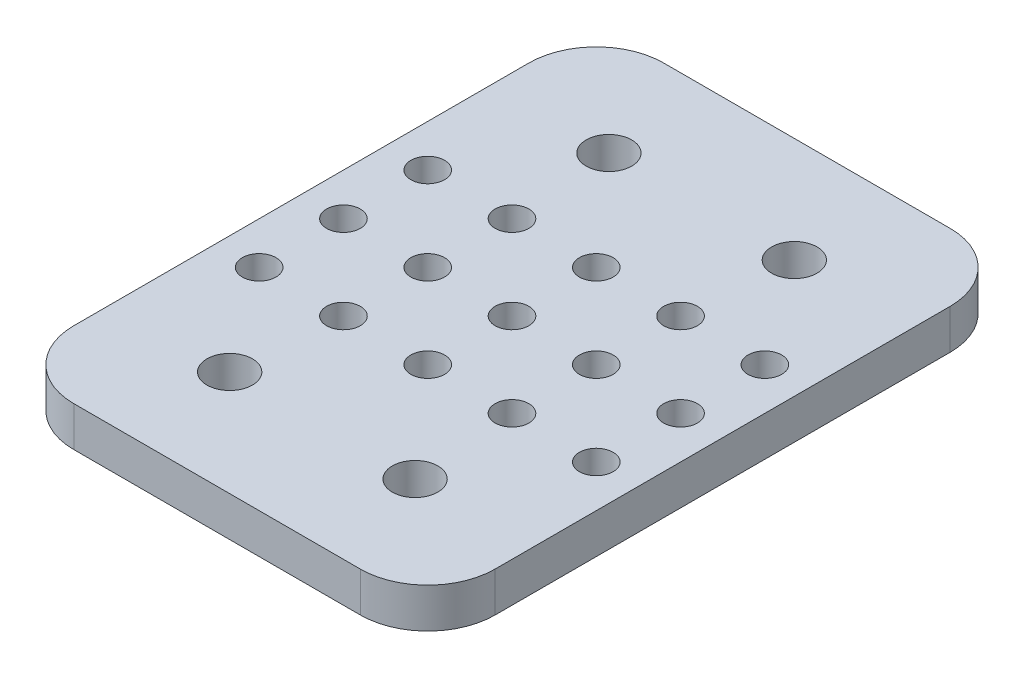
SolidWorks part; units mm, degrees
other "Markup1"
sketch "Sketch3" plane through (0, 6, 0) normal (-0.2556, 0.7181, 0.6473) x (0.9665, 0.2047, 0.1545)
ref_plane "Front Plane" through (0, 0, 0) normal (0, 0, 1) x (1, 0, 0)
ref_plane "Top Plane" through (0, 0, 0) normal (0, 1, 0) x (1, 0, 0)
ref_plane "Right Plane" through (0, 0, 0) normal (1, 0, 0) x (0, 0, -1)
sketch "Sketch1" plane through (0, 0, 0) normal (0, 1, 0) x (1, 0, 0)
  line L0 (31.75, 88.9) -> (31.75, 0) construction
  line L1 (0, 0) -> (63.5, 0)
  line L2 (0, 0) -> (0, 88.9)
  line L3 (0, 88.9) -> (63.5, 88.9)
  line L4 (63.5, 0) -> (63.5, 88.9)
  circle A0 centre (17.78, 73.025) radius 3.429
  circle A1 centre (45.72, 15.875) radius 3.429
  circle A2 centre (17.78, 15.875) radius 3.429
  circle A3 centre (45.72, 73.025) radius 3.429
  dimension "D3" = 57.15
  dimension "D4" = 27.94
  dimension "D5" = 6.858
  dimension "D6" = 15.875
  dimension "D7" = 17.78
  dimension "D1" = 63.5
  dimension "D2" = 88.9
extrude "Boss-Extrude1" add sketch "Sketch1" along normal blind 6
fillet "Fillet1" radius 10.16 4 edges at (0, 3, -88.9) (63.5, 3, -88.9) (63.5, 3, 0) (0, 3, 0)
sketch "Sketch2" plane through (0, 6, 0) normal (0, 1, 0) x (1, 0, 0)
  line L0 (0, 78.74) -> (0, 10.16) construction
  line L1 (0, 19.05) -> (63.5, 19.05) construction
  line L2 (0, 19.05) -> (0, 69.85)
  line L3 (0, 69.85) -> (63.5, 69.85) construction
  line L4 (63.5, 19.05) -> (63.5, 69.85)
  line L5 (63.5, 10.16) -> (63.5, 78.74) construction
  line L6 (53.34, 88.9) -> (10.16, 88.9) construction
  line L7 (6.35, 31.75) -> (19.05, 31.75) construction
  circle A0 centre (6.35, 57.15) radius 2.54
  circle A1 centre (6.35, 44.45) radius 2.54
  circle A2 centre (6.35, 31.75) radius 2.54
  circle A3 centre (19.05, 31.75) radius 2.54
  circle A4 centre (19.05, 44.45) radius 2.54
  circle A5 centre (19.05, 57.15) radius 2.54
  circle A6 centre (31.75, 31.75) radius 2.54
  circle A7 centre (31.75, 44.45) radius 2.54
  circle A8 centre (31.75, 57.15) radius 2.54
  circle A9 centre (44.45, 31.75) radius 2.54
  circle A10 centre (44.45, 44.45) radius 2.54
  circle A11 centre (44.45, 57.15) radius 2.54
  circle A12 centre (57.15, 31.75) radius 2.54
  circle A13 centre (57.15, 44.45) radius 2.54
  circle A14 centre (57.15, 57.15) radius 2.54
  dimension "D3" = 5.08
  dimension "D4" = 12.7
  dimension "D5" = 12.7
  dimension "D6" = 12.7
  dimension "D7" = 6.35
  dimension "D1" = 50.8
  dimension "D2" = 19.05
  dimension "D9" = 12.7
  dimension "D8" = 5
extrude "Cut-Extrude1" cut sketch "Sketch2" against normal through all contours A2 | A1 | A0 | A5 | A4 | A3 | A6 | A7 | A8 | A11 | A10 | A13 | A12 | A9 | A14
sketch "Sketch4" plane through (0, 0, 0) normal (0, -1, 0) x (-1, 0, 0)
  line L0 (-1000, 0) -> (49000, 0) construction
  line L2 (-63.5, -1000) -> (-63.5, 49000) construction
  line L3 (-63.5, 10.16) -> (-63.5, 78.74) construction
  point P6 (-63.5, 0)
  point P11 (0, 0)
  point P12 (0, 0)
